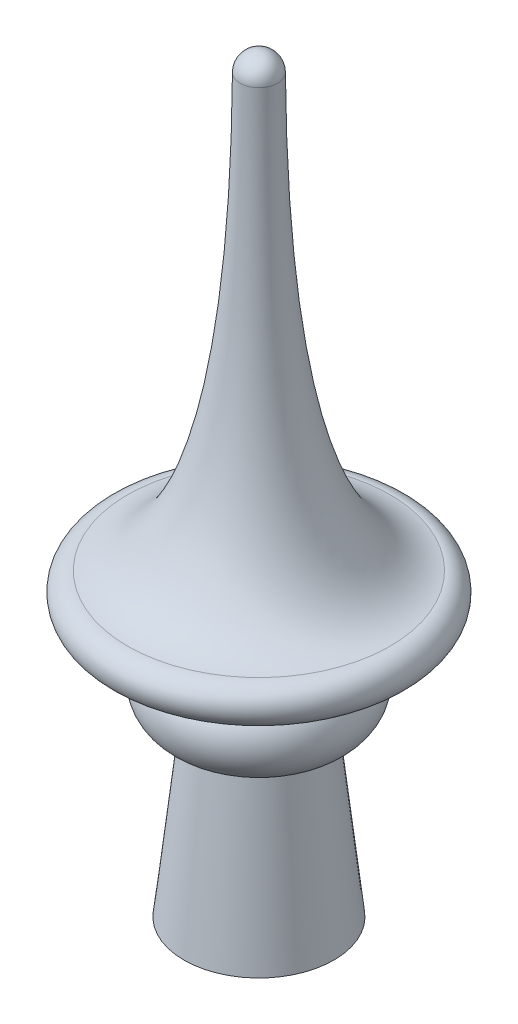
SolidWorks part; units mm, degrees
ref_plane "Front Plane" through (0, 0, 0) normal (0, 0, 1) x (1, 0, 0)
ref_plane "Top Plane" through (0, 0, 0) normal (0, 1, 0) x (1, 0, 0)
ref_plane "Right Plane" through (0, 0, 0) normal (1, 0, 0) x (0, 0, -1)
sketch "Sketch1" plane through (0, 0, 0) normal (0, 0, 1) x (1, 0, 0)
  line L0 (0, 0) -> (0, 200) construction
  line L1 (5, 195) -> (5, 80) construction
  line L2 (5, 80) -> (35, 80) construction
  line L3 (35, 80) -> (35, 70) construction
  line L4 (15, 70) -> (35, 70)
  line L5 (15, 70) -> (15, 65)
  line L6 (15, 65) -> (15, 45) construction
  line L7 (15, 45) -> (20, 0)
  line L8 (20, 0) -> (0, 0)
  line L9 (0, 200) -> (0, 0)
  arc A0 (0, 200) -> (5, 195) centre (0, 195) cw
  arc A1 (35, 80) -> (35, 70) centre (35, 75) cw
  arc A2 (15, 65) -> (15, 45) centre (15, 55) cw
  spline S0 degree 2 poles (5, 195) (5.7175, 84.9632) (35, 80) knots 0 0 0 1 1 1
  point P0 (35, 72.6937)
  point P2 (0, 424.8078)
  point P9 (0, 0)
  point P11 (10, 365.1548)
  point P15 (0, 0)
  point P16 (0, 0)
  point P17 (0, 0)
  point P18 (0, 0)
  point P22 (0, 0)
  point P23 (20.229, 88.6766)
  point P24 (0, 0)
  point P25 (0, 361.4322)
  point P26 (0, 0)
  dimension "D5" = 200
  dimension "D9" = 45
  dimension "D1" = 20
  dimension "D2" = 10
  dimension "D3" = 30
  dimension "D4" = 5
  dimension "D6" = 5
  dimension "D7" = 20
  dimension "D8" = 20
revolve "Revolve1" add sketch "Sketch1" angle 360 about L9
sketch "Sketch2" plane through (0, 0, 0) normal (0, -1, 0) x (1, 0, 0)
  circle A0 centre (0, 0) radius 12.5
  dimension "D1" = 25
extrude "Cut-Extrude1" cut sketch "Sketch2" against normal blind 70
